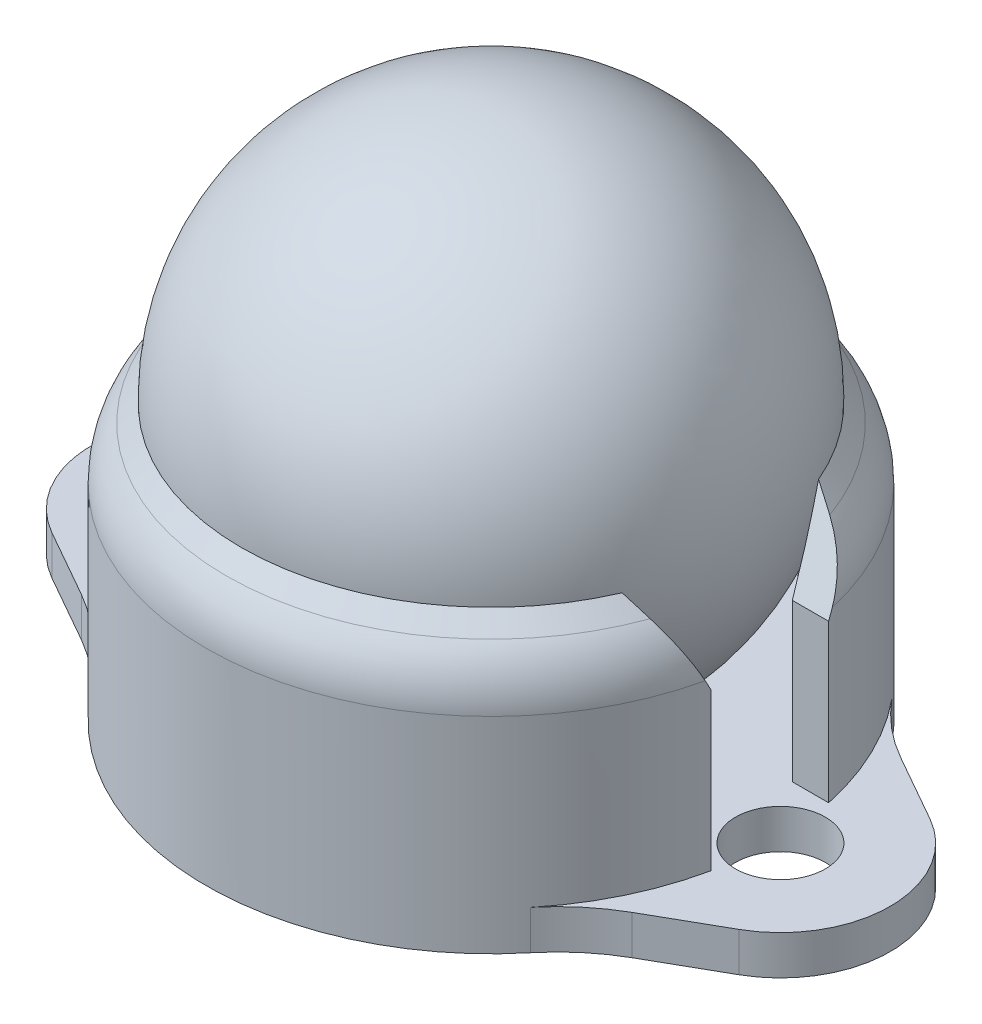
SolidWorks part; units mm, degrees
ref_plane "Přední rovina" through (0, 0, 0) normal (0, 0, 1) x (1, 0, 0)
ref_plane "Horní rovina" through (0, 0, 0) normal (0, 1, 0) x (1, 0, 0)
ref_plane "Pravá rovina" through (0, 0, 0) normal (1, 0, 0) x (0, 0, -1)
sketch "Skica1" plane through (0, 0, 0) normal (0, 1, 0) x (1, 0, 0)
  line L0 (10.16, 0) -> (-10.16, 0) construction
  line L1 (0, 0) -> (0, 5.7859) construction
  line L2 (-8.7453, 2.4298) -> (-7.0059, 3.4171)
  line L3 (-8.7453, -2.4298) -> (-7.0059, -3.4171)
  line L4 (8.7453, -2.4298) -> (7.0059, -3.4171)
  line L5 (8.7453, 2.4298) -> (7.0059, 3.4171)
  arc A0 (7.0059, -3.4171) -> (5.6072, -4.5959) centre (9.4742, -7.7654) ccw
  circle A1 centre (-7.366, 0) radius 1.143
  arc A2 (-8.7453, 2.4298) -> (-8.7453, -2.4298) centre (-7.366, 0) ccw
  arc A3 (-7.0059, 3.4171) -> (-5.6072, 4.5959) centre (-9.4742, 7.7654) ccw
  arc A4 (-7.0059, -3.4171) -> (-5.6072, -4.5959) centre (-9.4742, -7.7654) cw
  arc A5 (-5.6072, -4.5959) -> (5.6072, -4.5959) centre (0, 0) ccw
  circle A6 centre (7.366, 0) radius 1.143
  arc A7 (8.7453, 2.4298) -> (8.7453, -2.4298) centre (7.366, 0) cw
  arc A8 (7.0059, 3.4171) -> (5.6072, 4.5959) centre (9.4742, 7.7654) cw
  arc A9 (5.6072, 4.5959) -> (-5.6072, 4.5959) centre (0, 0) ccw
  dimension "D1" = 20.32
  dimension "D2" = 2.286
  dimension "D3" = 14.732
  dimension "D4" = 7.25
  dimension "D5" = 5
  dimension "D6" = 2
extrude "Přidat vysunutím1" add sketch "Skica1" along normal blind 1
sketch "Skica2" plane through (0, 0, 0) normal (0, 0, 1) x (1, 0, 0)
  line L0 (-5.6072, 0) -> (5.6072, 0) construction
  line L1 (0, 0) -> (0, 14.4673) construction
  line L2 (0, 13.462) -> (0, 0.762)
  arc A0 (0, 0.762) -> (0, 13.462) centre (0, 7.112) ccw
  dimension "D1" = 13.462
  dimension "D2" = 12.7
revolve "Rotovat2" add sketch "Skica2" angle 360 about L1
sketch "Skica3" plane through (0, 0, 0) normal (1, 0, 0) x (0, 0, -1)
  line L0 (7.25, 1) -> (7.25, 5.2319)
  line L1 (6.7359, 6.5706) -> (6.349, 7)
  line L2 (6.349, 7) -> (6.349, 1)
  line L4 (7.25, 1) -> (4.5959, 1) construction
  line L6 (6.349, 1) -> (7.25, 1)
  line L8 (2.4298, 1) -> (-2.4298, 1) construction
  line L9 (0, 0) -> (0, 9.3673) construction
  circle A0 centre (0, 7.112) radius 6.35 construction
  arc A1 (7.25, 5.2319) -> (6.7359, 6.5706) centre (5.25, 5.2319) ccw
  circle A2 centre (0, 7.112) radius 6.35 construction
  point P9 (7.25, 6)
  dimension "D3" = 2
  dimension "D2" = 5
  dimension "D5" = 6
revolve "Rotovat5" add sketch "Skica3" angle 360 about L9
sketch "Skica4" plane through (0, 0, 0) normal (1, 0, 0) x (0, 0, -1)
  line L0 (-2.5, 7) -> (-1.5, 5)
  line L2 (-1.5, 5) -> (-1.5, 1)
  line L3 (-1.1247, 1) -> (-4.5959, 1) construction
  line L4 (0, 0) -> (0, 10.4938) construction
  line L5 (1.5, 5) -> (1.5, 1)
  line L6 (2.5, 7) -> (1.5, 5)
  line L7 (-2.5, 7) -> (2.5, 7)
  line L8 (-1.5, 1) -> (1.5, 1)
  line L9 (1.5, 1) -> (1.4592, 2.0553)
  line L10 (6.349, 7) -> (-6.349, 7) construction
  dimension "D1" = 3
  dimension "D2" = 5
  dimension "D3" = 4
extrude "Odebrat vysunutím1" cut sketch "Skica4" against normal through all and the other way through all contours L5 L6 L7 L0 L2 L8
